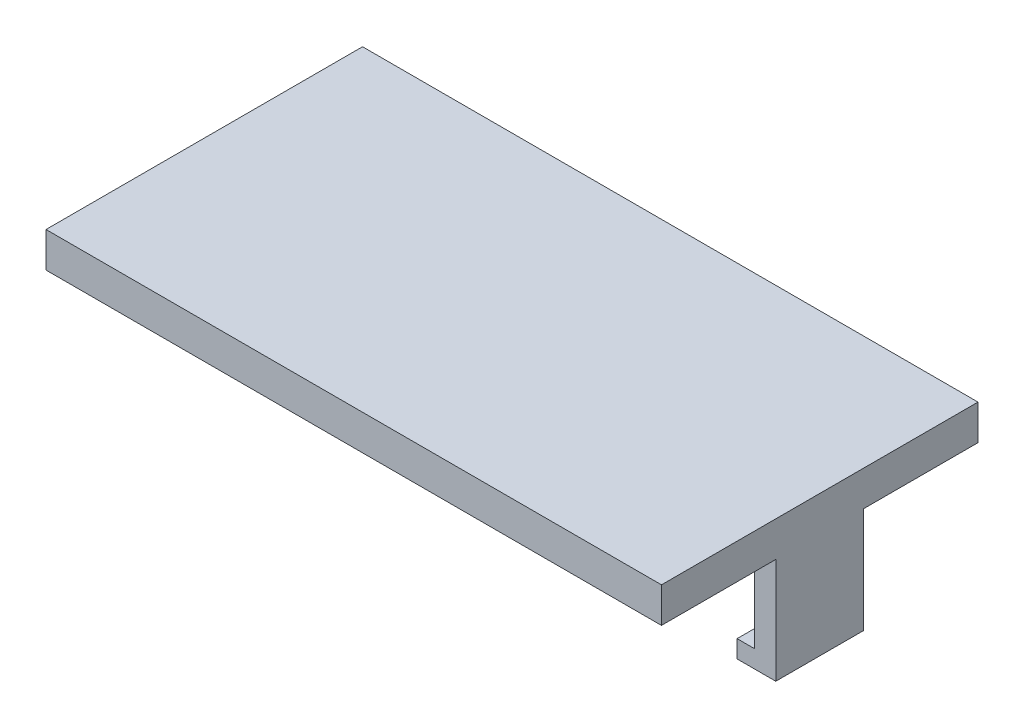
SolidWorks part; units mm, degrees
ref_plane "Front Plane" through (0, 0, 0) normal (0, 0, 1) x (1, 0, 0)
ref_plane "Top Plane" through (0, 0, 0) normal (0, 1, 0) x (1, 0, 0)
ref_plane "Right Plane" through (0, 0, 0) normal (1, 0, 0) x (0, 0, -1)
sketch "Sketch1" plane through (0, 0, 0) normal (0, 1, 0) x (1, 0, 0)
  line L1 (-17.5, -9) -> (17.5, -9)
  line L2 (-17.5, -9) -> (-17.5, 9)
  line L3 (-17.5, 9) -> (17.5, 9)
  line L4 (17.5, -9) -> (17.5, 9)
  line L5 (-17.5, -9) -> (17.5, 9) construction
  line L6 (-17.5, 9) -> (17.5, -9) construction
  point P0 (0, 0)
  dimension "D1" = 35
  dimension "D2" = 18
extrude "Boss-Extrude1" add sketch "Sketch1" along normal blind 2
sketch "Sketch2" plane through (17.5, 0, 0) normal (1, 0, 0) x (0, 0, -1)
  line L1 (-2.5, 0) -> (2.5, 0)
  line L2 (-2.5, 0) -> (-2.5, -6)
  line L3 (-2.5, -6) -> (2.5, -6)
  line L4 (2.5, 0) -> (2.5, -6)
  line L5 (-2.5, 0) -> (2.5, -6) construction
  line L6 (-2.5, -6) -> (2.5, 0) construction
  point P0 (0, -3)
  point P9 (0, 0)
  dimension "D1" = 5
  dimension "D2" = 6
extrude "Boss-Extrude2" add sketch "Sketch2" against normal blind 1.2
sketch "Sketch3" plane through (16.3, 0, 0) normal (-1, 0, 0) x (0, 0, 1)
  line L5 (2.5, 0) -> (2.5, -6) construction
  line L6 (-2.5, -6) -> (2.5, -6)
  line L7 (-2.5, -6) -> (-2.5, -5)
  line L8 (-2.5, -5) -> (2.5, -5)
  line L9 (2.5, -6) -> (2.5, -5)
  dimension "D1" = 1
extrude "Boss-Extrude3" add sketch "Sketch3" along normal blind 1
mirror "Mirror1" about plane through (0, 0, 0) normal (1, 0, 0) of "Boss-Extrude2", "Boss-Extrude3"
